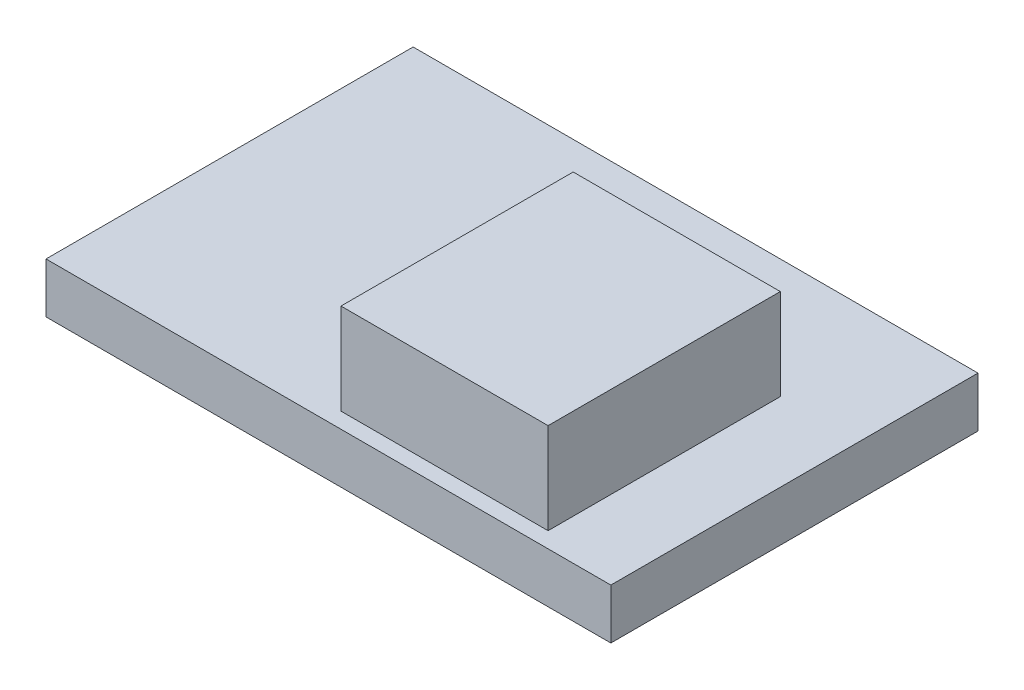
SolidWorks part; units mm, degrees
ref_plane "Ebene vorne" through (0, 0, 0) normal (0, 0, 1) x (1, 0, 0)
ref_plane "Ebene oben" through (0, 0, 0) normal (0, 1, 0) x (1, 0, 0)
ref_plane "Ebene rechts" through (0, 0, 0) normal (1, 0, 0) x (0, 0, -1)
sketch "Sketch1" plane through (0, 0, 0) normal (0, 1, 0) x (1, 0, 0)
  line L0 (0, 5.85) -> (0, -5.85) construction
  line L1 (-9, 5.85) -> (9, 5.85)
  line L2 (-9, 5.85) -> (-9, -5.85)
  line L3 (-9, -5.85) -> (9, -5.85)
  line L4 (9, 5.85) -> (9, -5.85)
  line L5 (-9, 0) -> (9, 0) construction
  point P10 (0, 0)
  dimension "D1" = 11.7
  dimension "D2" = 18
extrude "Boss-Extrude1" add sketch "Sketch1" along normal blind 1.6
sketch "Sketch2" plane through (0, 1.6, 0) normal (0, 1, 0) x (1, 0, 0)
  line L0 (9, -5.85) -> (9, 5.85) construction
  line L1 (-0.1, 2.05) -> (6.5, 2.05)
  line L2 (-0.1, 2.05) -> (-0.1, -5.35)
  line L3 (-0.1, -5.35) -> (6.5, -5.35)
  line L4 (6.5, 2.05) -> (6.5, -5.35)
  line L5 (-9, -5.85) -> (9, -5.85) construction
  dimension "D1" = 7.4
  dimension "D2" = 6.6
  dimension "D3" = 2.5
  dimension "D4" = 0.5
extrude "Boss-Extrude2" add sketch "Sketch2" along normal blind 2.9
